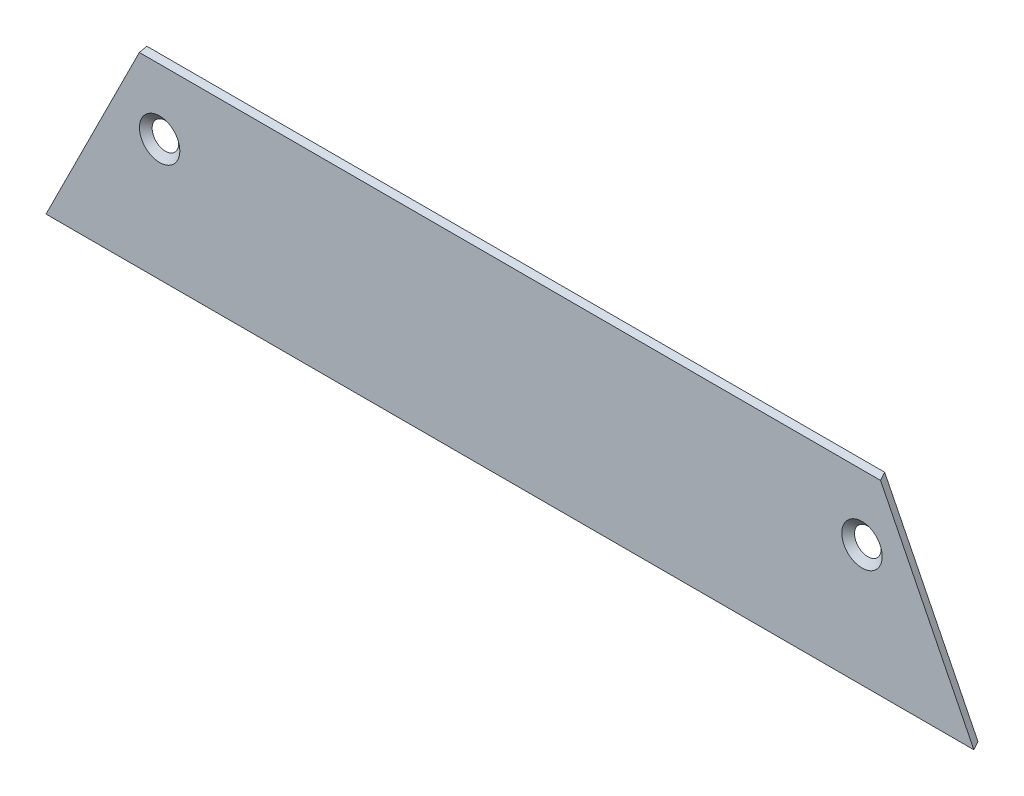
SolidWorks part; units mm, degrees
material "1023 Carbon Steel Sheet (SS)"
ref_plane "Front Plane" through (0, 0, 0) normal (0, 0, 1) x (1, 0, 0)
ref_plane "Top Plane" through (0, 0, 0) normal (0, 1, 0) x (1, 0, 0)
ref_plane "Right Plane" through (0, 0, 0) normal (1, 0, 0) x (0, 0, -1)
sketch "Sketch3" plane through (0, 0, 0) normal (1, 0, 0) x (0, 0, -1)
  line L0 (-0.5715, 31.42) -> (-1.5875, 30.8335)
  line L2 (-0.5715, -1.3309) -> (-0.5715, 31.42)
  line L3 (-1.5875, -1.9175) -> (-0.5715, -1.3309)
  line L4 (-1.5875, -1.9175) -> (-1.5875, 30.8335)
  dimension "D1" = 60
  dimension "D2" = 1.016
  dimension "D3" = 60
  dimension "D4" = 33.3375
extrude "Boss-Extrude2" add sketch "Sketch3" along normal blind 162.814
sketch "Sketch5" plane through (0, 0, 1.5875) normal (0, 0, 1) x (1, 0, 0)
  line L0 (0, -1.9175) -> (16.6723, 31.42)
  line L2 (16.6723, 31.42) -> (0, 31.42)
  line L3 (0, 31.42) -> (0, -1.9175)
  line L4 (162.814, -1.9175) -> (146.1417, 31.42)
  line L5 (146.1417, 31.42) -> (162.814, 31.42)
  line L6 (162.814, 31.42) -> (162.814, -1.9175)
  dimension "D1" = 26.57
  dimension "D2" = 26.57
extrude "Cut-Extrude1" cut sketch "Sketch5" against normal through all
hole_wizard "CSK for #6 Flat Head Machine Screw (100)1" positions "Sketch8" profile "Sketch7" countersink size "#6" standard "ANSI Inch" end condition through all
sketch "Sketch8" plane through (0, 0, 1.5875) normal (0, 0, 1) x (1, 0, 0)
  point P0 (19.939, 19.427)
  point P3 (143.1874, 19.427)
  point P6 (143.1874, 19.427)
sketch "Sketch7" plane through (19.939, 19.427, 1.5875) normal (1, 0, 0) x (0, -1, 0)
  line L0 (0, 0) -> (0, 1.016)
  line L1 (0, 1.016) -> (1.8986, 1.016)
  line L2 (1.8986, 1.016) -> (1.8986, 1.38)
  line L3 (1.8986, 1.38) -> (3.5433, 0)
  line L5 (3.5433, 0) -> (0, 0)
  line L6 (-1.8987, 1.38) -> (-3.5433, 0) construction
  line L11 (0, -6.35) -> (0, 107.95) construction
  dimension "Thru Hole Dia." = 3.7973
  dimension "Thru Hole Depth" = 1.016
  dimension "Near C'Sink Dia." = 7.0866
  dimension "Near C'Sink Angle" = 100
